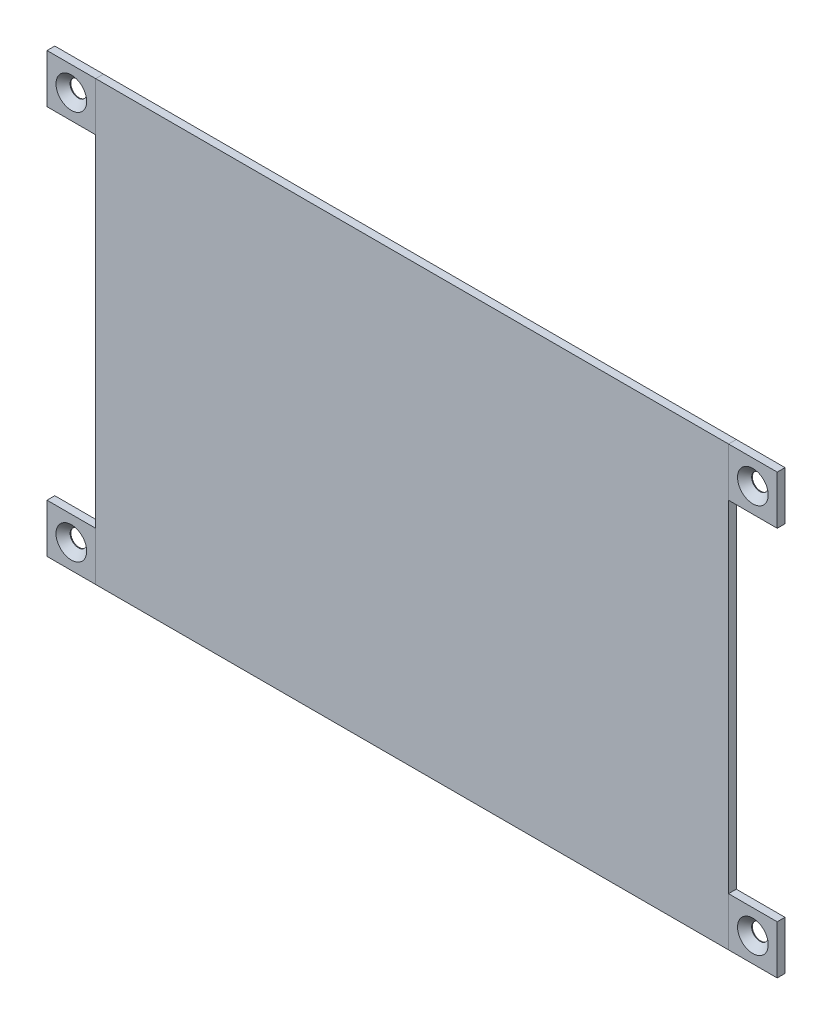
SolidWorks part; units mm, degrees
ref_plane "Front Plane" through (0, 0, 0) normal (0, 0, 1) x (1, 0, 0)
ref_plane "Top Plane" through (0, 0, 0) normal (0, 1, 0) x (1, 0, 0)
ref_plane "Right Plane" through (0, 0, 0) normal (1, 0, 0) x (0, 0, -1)
sketch "Sketch1" plane through (0, 0, 0) normal (0, 0, 1) x (1, 0, 0)
  line L1 (0, 0) -> (130, 0)
  line L2 (0, 0) -> (0, 90)
  line L3 (0, 90) -> (130, 90)
  line L4 (130, 0) -> (130, 90)
  dimension "D1" = 90
  dimension "D2" = 130
extrude "Boss-Extrude1" add sketch "Sketch1" along normal blind 1.6
sketch "Sketch2" plane through (0, 0, 0) normal (0, 0, -1) x (-1, 0, 0)
  line L1 (-130, 90) -> (-140, 90)
  line L2 (-130, 90) -> (-130, 80)
  line L3 (-130, 80) -> (-140, 80)
  line L4 (-140, 90) -> (-140, 80)
  line L5 (-130, 0) -> (-140, 0)
  line L6 (-130, 0) -> (-130, 10)
  line L7 (-130, 10) -> (-140, 10)
  line L8 (-140, 0) -> (-140, 10)
  line L9 (0, 0) -> (10, 0)
  line L10 (0, 0) -> (0, 10)
  line L11 (0, 10) -> (10, 10)
  line L12 (10, 0) -> (10, 10)
  line L13 (0, 90) -> (10, 90)
  line L14 (0, 90) -> (0, 80)
  line L15 (0, 80) -> (10, 80)
  line L16 (10, 90) -> (10, 80)
  dimension "D1" = 10
extrude "Boss-Extrude2" add sketch "Sketch2" against normal blind 1.6 separate body
hole_wizard "CSK for M3 Countersunk Flat Head Screw1" positions "Sketch4" profile "Sketch5" countersink size "M3" standard "ISO"
sketch "Sketch4" plane through (0, 0, 1.6) normal (0, 0, 1) x (1, 0, 0)
  point P0 (-5, 85)
  point P2 (135, 85)
  point P4 (135, 5)
  point P6 (-5, 5)
sketch "Sketch5" plane through (-5, 85, 1.6) normal (1, 0, 0) x (0, -1, 0)
  line L0 (0, 0) -> (0, 31.0215)
  line L1 (0, 31.0215) -> (1.7, 30)
  line L2 (1.7, 30) -> (1.7, 1.45)
  line L3 (1.7, 1.45) -> (3.15, 0)
  line L5 (3.15, 0) -> (0, 0)
  line L6 (-1.7, 1.45) -> (-3.15, 0) construction
  line L10 (0, 31.0215) -> (-1.7, 30) construction
  line L11 (0, -6.35) -> (0, 107.95) construction
  dimension "Hole Dia." = 3.4
  dimension "Hole Depth" = 30
  dimension "Near C'Sink Dia." = 6.3
  dimension "Near C'Sink Angle" = 90
  dimension "Drill Angle" = 118
